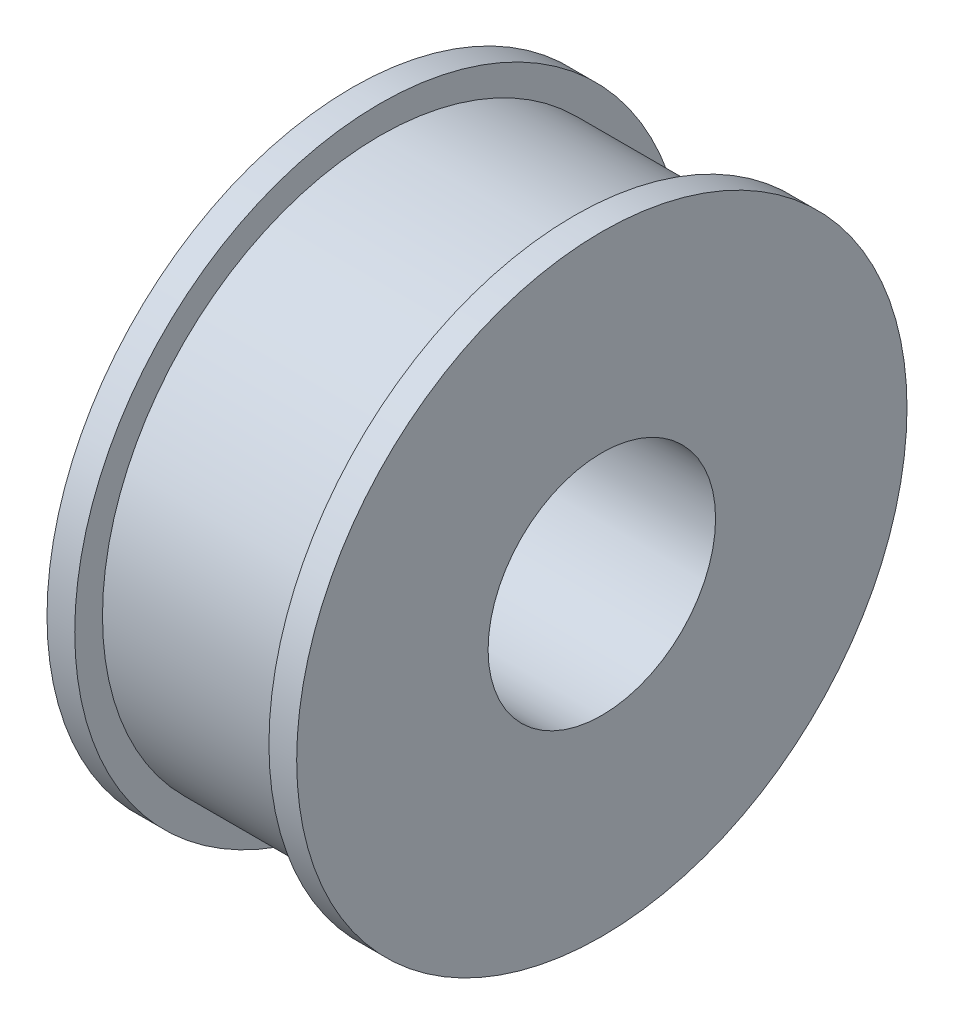
SolidWorks part; units mm, degrees
ref_plane "Front Plane" through (0, 0, 0) normal (0, 0, 1) x (1, 0, 0)
ref_plane "Top Plane" through (0, 0, 0) normal (0, 1, 0) x (1, 0, 0)
ref_plane "Right Plane" through (0, 0, 0) normal (1, 0, 0) x (0, 0, -1)
sketch "Sketch1" plane through (0, 0, 0) normal (0, 0, 1) x (1, 0, 0)
  line L0 (0, 0) -> (5.1881, 0) construction
  line L2 (-5.5, -0.875) -> (-5.5, 11) construction
  line L3 (-5.5, 11) -> (3.5, 11)
  line L4 (3.5, 4.1) -> (3.5, 11)
  line L5 (-5.5, 11) -> (-5.5, 4.1)
  line L8 (-5.5, 4.1) -> (3.5, 4.1)
  dimension "D1" = 11
  dimension "D2" = 9
  dimension "D5" = 4.1
revolve "Revolve1" add sketch "Sketch1" angle 360 about L0
sketch "Sketch2" plane through (0, 0, 0) normal (0, 0, 1) x (1, 0, 0)
  line L6 (0, 0) -> (5.4705, 0) construction
  line L9 (3.5, 3.3693) -> (3.5, 11) construction
  line L10 (3.5, 11) -> (2.5, 11) construction
  line L11 (2.5, 11) -> (2.5, 10) construction
  line L12 (2.5, 10) -> (-5.5, 10) construction
  line L13 (-5.5, 10) -> (-5.5, 3.3693) construction
  line L14 (3.5, 11) -> (-5.5, 11) construction
  line L15 (3.5, -11) -> (3.5, 11) construction
  line L16 (-5.5, 11) -> (-5.5, -11) construction
  line L17 (2.5, 10) -> (2.5, 11)
  line L18 (2.5, 11) -> (-4.5, 11)
  line L20 (-4.5, 11) -> (-4.5, 10)
  line L21 (-4.5, 10) -> (2.5, 10)
  dimension "D1" = 10
  dimension "D2" = 1
  dimension "D3" = 1
revolve "Cut-Revolve1" cut sketch "Sketch2" angle 360 about L6
